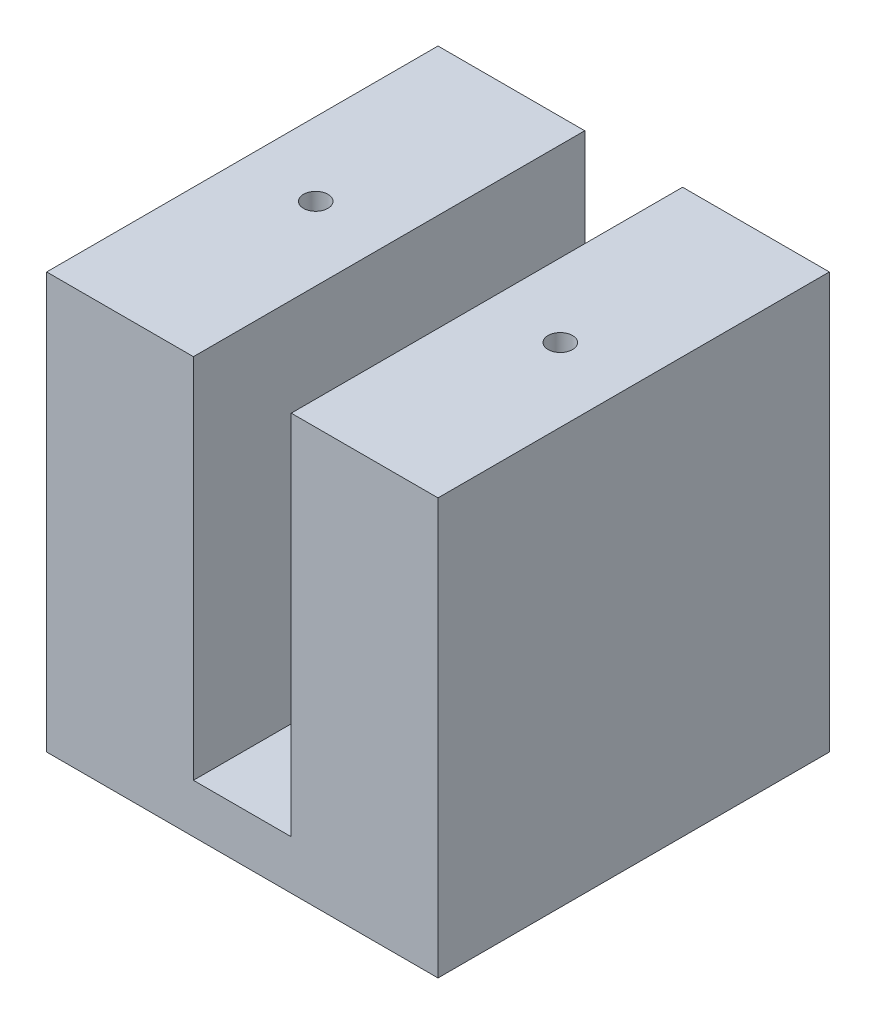
SolidWorks part; units mm, degrees
ref_plane "Front Plane" through (0, 0, 0) normal (0, 0, 1) x (1, 0, 0)
ref_plane "Top Plane" through (0, 0, 0) normal (0, 1, 0) x (1, 0, 0)
ref_plane "Right Plane" through (0, 0, 0) normal (1, 0, 0) x (0, 0, -1)
sketch "Sketch1" plane through (0, 0, 0) normal (0, 1, 0) x (1, 0, 0)
  line L1 (-25.4, -25.4) -> (25.4, -25.4)
  line L2 (-25.4, -25.4) -> (-25.4, 25.4)
  line L3 (-25.4, 25.4) -> (25.4, 25.4)
  line L4 (25.4, -25.4) -> (25.4, 25.4)
  line L5 (-25.4, -25.4) -> (25.4, 25.4) construction
  line L6 (-25.4, 25.4) -> (25.4, -25.4) construction
  point P0 (0, 0)
  dimension "D1" = 50.8
  dimension "D2" = 50.8
extrude "Boss-Extrude1" add sketch "Sketch1" along normal blind 6.35
sketch "Sketch2" plane through (0, 6.35, 0) normal (0, 1, 0) x (1, 0, 0)
  line L0 (-25.4, -25.4) -> (25.4, -25.4) construction
  line L1 (-25.4, 25.4) -> (-6.35, 25.4)
  line L2 (-25.4, 25.4) -> (-25.4, -25.4)
  line L3 (-25.4, -25.4) -> (-6.35, -25.4)
  line L4 (-6.35, 25.4) -> (-6.35, -25.4)
  line L6 (25.4, 25.4) -> (6.35, 25.4)
  line L7 (25.4, 25.4) -> (25.4, -25.4)
  line L8 (25.4, -25.4) -> (6.35, -25.4)
  line L9 (6.35, 25.4) -> (6.35, -25.4)
  dimension "D1" = 6.35
  dimension "D2" = 6.35
extrude "Boss-Extrude2" add sketch "Sketch2" along normal blind 47.625
sketch "Sketch3" plane through (0, 6.35, 0) normal (0, 1, 0) x (1, 0, 0)
  line L0 (0, 25.4) -> (0, -25.4) construction
  line L1 (6.35, 25.4) -> (-6.35, 25.4) construction
  line L2 (-6.35, -25.4) -> (6.35, -25.4) construction
  circle A0 centre (0, 6.35) radius 1.5875
  circle A1 centre (0, -6.35) radius 1.5875
  point P11 (-1.5217, 6.165)
  point P12 (-2.291, -5.9223)
  dimension "D1" = 3.175
  dimension "D2" = 6.35
  dimension "D3" = 6.35
extrude "Cut-Extrude1" cut sketch "Sketch3" against normal through all
sketch "Sketch4" plane through (0, 53.975, 0) normal (0, 1, 0) x (1, 0, 0)
  line L0 (-25.4, 0) -> (25.4, 0) construction
  line L1 (-25.4, 25.4) -> (-25.4, -25.4) construction
  line L2 (25.4, -25.4) -> (25.4, 25.4) construction
  circle A0 centre (-15.875, 0) radius 1.5875
  circle A1 centre (15.875, 0) radius 1.5875
  point P11 (0, 0)
  point P12 (0, 0)
  dimension "D3" = 3.175
  dimension "D1" = 15.875
  dimension "D2" = 15.875
extrude "Cut-Extrude2" cut sketch "Sketch4" against normal through all
